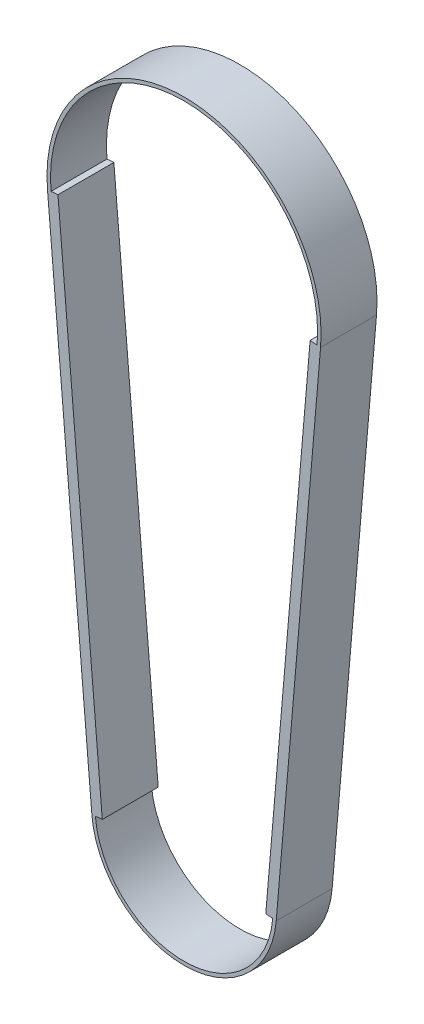
SolidWorks part; units mm, degrees
material "Rubber"
ref_plane "Front Plane" through (0, 0, 0) normal (0, 0, 1) x (1, 0, 0)
ref_plane "Top Plane" through (0, 0, 0) normal (0, 1, 0) x (1, 0, 0)
ref_plane "Right Plane" through (0, 0, 0) normal (1, 0, 0) x (0, 0, -1)
sketch "Sketch1" plane through (0, 0, 0) normal (0, 0, 1) x (1, 0, 0)
  line L0 (-76.1129, -6.5065) -> (-50.7419, -303.2957)
  line L1 (0, 0) -> (0, -298.958) construction
  line L2 (76.1129, -6.5065) -> (50.7419, -303.2957)
  line L3 (-78.1056, -6.6768) -> (-52.7347, -303.466)
  line L4 (52.7347, -303.466) -> (78.1056, -6.6768)
  line L11 (78.1056, -6.6768) -> (52.7347, -303.466) construction
  line L12 (76.1129, -6.5065) -> (50.7419, -303.2957) construction
  arc A0 (76.1129, -6.5065) -> (-76.1129, -6.5065) centre (0, 0) ccw
  arc A1 (-50.7419, -303.2957) -> (50.7419, -303.2957) centre (0, -298.958) ccw
  arc A2 (78.1056, -6.6768) -> (-78.1056, -6.6768) centre (0, 0) ccw
  arc A3 (-52.7347, -303.466) -> (52.7347, -303.466) centre (0, -298.958) ccw
  dimension "D1" = 152.781
  dimension "D2" = 101.854
  dimension "D3" = 298.958
  dimension "D4" = 2
extrude "Boss-Extrude1" add sketch "Sketch1" along normal blind 32
sketch "Sketch2" plane through (76.1129, -6.5065, 0) normal (-0.9964, 0.0852, 0) x (0, 0, 1)
  line L4 (0, 0) -> (0, -297.8716)
  line L5 (0, -297.8716) -> (32, -297.8716)
  line L6 (32, -297.8716) -> (32, 0)
  line L7 (32, 0) -> (0, 0)
  line L8 (0, 0) -> (0, -297.8716)
  line L9 (0, -297.8716) -> (32, -297.8716)
  line L10 (32, -297.8716) -> (32, 0)
  line L11 (32, 0) -> (0, 0)
  dimension "D1" = 0
extrude "Boss-Extrude2" add sketch "Sketch2" along normal blind 4
sketch "Sketch3" plane through (-76.1129, -6.5065, 0) normal (0.9964, 0.0852, 0) x (0, 0, -1)
  line L4 (0, -297.8716) -> (0, 0)
  line L5 (0, 0) -> (-32, 0)
  line L6 (-32, 0) -> (-32, -297.8716)
  line L7 (-32, -297.8716) -> (0, -297.8716)
  line L8 (0, -297.8716) -> (0, 0)
  line L9 (0, 0) -> (-32, 0)
  line L10 (-32, 0) -> (-32, -297.8716)
  line L11 (-32, -297.8716) -> (0, -297.8716)
  dimension "D1" = 0
extrude "Boss-Extrude3" add sketch "Sketch3" along normal blind 4
other "Freeze***"
